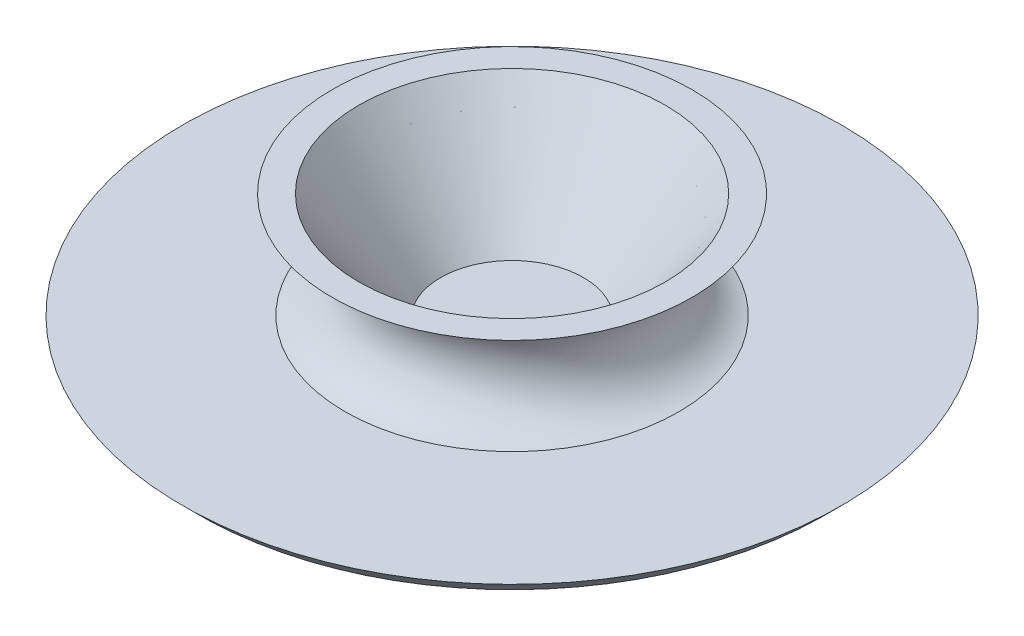
SolidWorks part; units mm, degrees
ref_plane "Front Plane" through (0, 0, 0) normal (0, 0, 1) x (1, 0, 0)
ref_plane "Top Plane" through (0, 0, 0) normal (0, 1, 0) x (1, 0, 0)
ref_plane "Right Plane" through (0, 0, 0) normal (1, 0, 0) x (0, 0, -1)
sketch "Sketch1" plane through (0, 0, 0) normal (0, 0, 1) x (1, 0, 0)
  line L0 (0, 0) -> (0, 35.8927) construction
  line L1 (0, 0) -> (-23.6684, 0)
  line L2 (-23.6684, 0) -> (-27.8299, 4.1615)
  line L3 (-27.8299, 4.1615) -> (-72.3056, 4.1615)
  line L4 (-72.3056, 4.1615) -> (-75.9469, 7.8028)
  line L5 (-75.9469, 7.8028) -> (0, 7.8028)
  line L6 (0, 7.8028) -> (0, 0)
revolve "Revolve1" add sketch "Sketch1" angle 360 about L0
sketch "Sketch2" plane through (0, 0, 0) normal (0, 0, 1) x (1, 0, 0)
  line L0 (75.9469, 7.8028) -> (-75.9469, 7.8028) construction
  line L1 (0, 0) -> (0, 44.4352) construction
  line L2 (-41.4765, 32.1025) -> (0, 32.1025)
  line L3 (0, 32.1025) -> (0, 7.8028)
  line L4 (-38.4915, 7.8028) -> (0, 7.8028)
  arc A0 (-38.4915, 7.8028) -> (-41.4765, 32.1025) centre (-41.4765, 19.7693) ccw
  dimension "D1" = 12.3332
revolve "Revolve2" add sketch "Sketch2" angle 360 about L1
sketch "Sketch3" plane through (0, 32.1025, 0) normal (0, 1, 0) x (1, 0, 0)
  circle A0 centre (0, 0) radius 35.3045
extrude "Cut-Extrude2" cut sketch "Sketch3" against normal blind 25 draft 37
